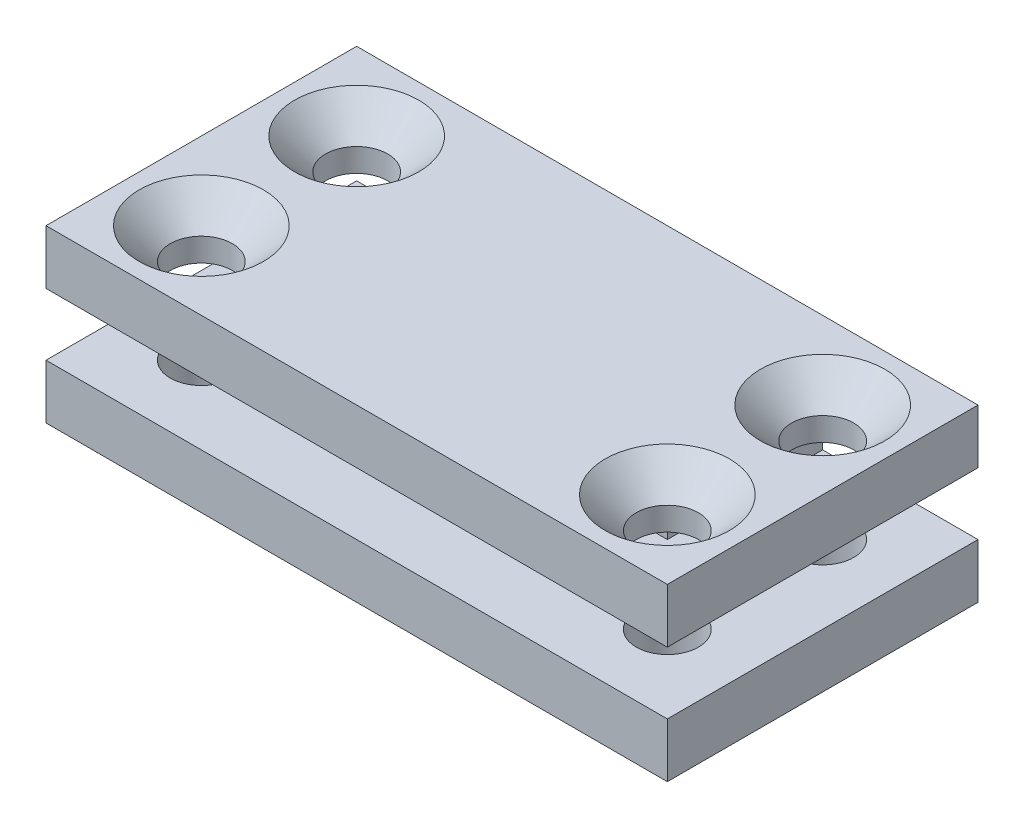
SolidWorks part; units mm, degrees
material "1060 合金"
ref_plane "前视基准面" through (0, 0, 0) normal (0, 0, 1) x (1, 0, 0)
ref_plane "上视基准面" through (0, 0, 0) normal (0, 1, 0) x (1, 0, 0)
ref_plane "右视基准面" through (0, 0, 0) normal (1, 0, 0) x (0, 0, -1)
sketch "草图1" plane through (0, 0, 0) normal (0, 0, 1) x (1, 0, 0)
  line L0 (0, -9.5783) -> (0, 32.1084) construction
  line L9 (20, 11) -> (-20, 11)
  line L11 (-10, 3.5) -> (-20, 3.5)
  line L12 (-20, 3.5) -> (-20, 0)
  line L13 (-20, 0) -> (0, 0)
  line L14 (20, 0) -> (0, 0)
  line L15 (20, 3.5) -> (20, 0)
  line L16 (10, 3.5) -> (20, 3.5)
  line L18 (0, -3) -> (-12.7922, -3) construction
  line L19 (-20, 11) -> (-20, 7.5)
  line L20 (-20, 7.5) -> (-10, 7.5)
  line L21 (-10, 7.5) -> (-10, 3.5)
  line L22 (10, 7.5) -> (10, 3.5)
  line L23 (20, 7.5) -> (10, 7.5)
  line L24 (20, 11) -> (20, 7.5)
  circle A0 centre (0, 5) radius 1.5
  circle A1 centre (0, 5) radius 8 construction
  circle A2 centre (0, 5) radius 6 construction
  point P10 (-10, 0)
  point P15 (0, 11)
  point P26 (-10, 5.5)
  dimension "D5" = 3
  dimension "D7" = 16
  dimension "D8" = 12
  dimension "D1" = 3.5
  dimension "D2" = 6.5
  dimension "D3" = 4
  dimension "D4" = 10
  dimension "D6" = 20
extrude "凸台-拉伸1" add sketch "草图1" along normal mid plane 10
sketch "草图3" plane through (0, 0, 5) normal (0, 0, 1) x (1, 0, 0)
  line L1 (-20, 11) -> (20, 11)
  line L2 (-20, 11) -> (-20, 7.5)
  line L3 (-20, 7.5) -> (20, 7.5)
  line L4 (20, 11) -> (20, 7.5)
  line L5 (20, 3.5) -> (-20, 3.5)
  line L6 (20, 3.5) -> (20, 0)
  line L7 (20, 0) -> (-20, 0)
  line L8 (-20, 3.5) -> (-20, 0)
extrude "凸台-拉伸2" add sketch "草图3" along normal blind 10
sketch "草图2" plane through (0, 0, 0) normal (0, 1, 0) x (1, 0, 0)
  line L0 (0, 5) -> (0, -5) construction
  line L1 (20, 5) -> (-20, 5) construction
  line L2 (20, -5) -> (-20, -5) construction
  line L3 (-20, -15) -> (-20, 5) construction
  line L4 (20, -15) -> (-20, -15) construction
  line L5 (-20, -15) -> (-20, 5) construction
  circle A0 centre (-15, 0) radius 2
  circle A1 centre (15, 0) radius 2
  circle A2 centre (-15, -10) radius 2
  circle A3 centre (15, -10) radius 2
  dimension "D1" = 4
  dimension "D2" = 5
  dimension "D3" = 5
  dimension "D4" = 5
extrude "切除-拉伸1" cut sketch "草图2" along normal through all
chamfer "倒角1" distance 2 angle 45 4 edges at (-15, 11, 2) (-15, 11, 12) (15, 11, 8) (15, 11, -2)
